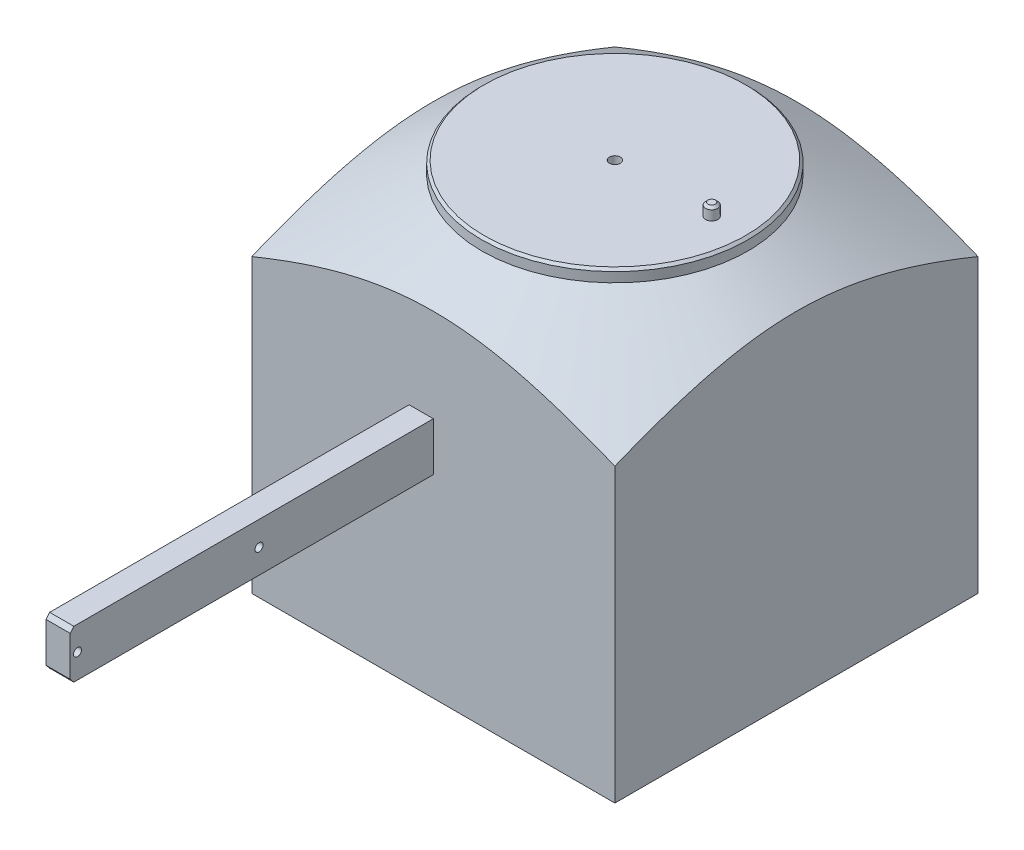
SolidWorks part; units mm, degrees
ref_plane "Płaszczyzna przednia" through (0, 0, 0) normal (0, 0, 1) x (1, 0, 0)
ref_plane "Płaszczyzna górna" through (0, 0, 0) normal (0, 1, 0) x (1, 0, 0)
ref_plane "Płaszczyzna prawa" through (0, 0, 0) normal (1, 0, 0) x (0, 0, -1)
sketch "Sketch1" plane through (0, 0, 0) normal (0, 1, 0) x (1, 0, 0)
  line L1 (-150, 150) -> (150, 150)
  line L2 (-150, 150) -> (-150, -150)
  line L3 (-150, -150) -> (150, -150)
  line L4 (150, 150) -> (150, -150)
  line L5 (-150, 150) -> (150, -150) construction
  line L6 (-150, -150) -> (150, 150) construction
  point P0 (0, 0)
  dimension "D1" = 300
extrude "Boss-Extrude1" add sketch "Sketch1" along normal blind 300
sketch "Sketch2" plane through (0, 0, 0) normal (0, 0, 1) x (1, 0, 0)
  line L0 (0, 394.1921) -> (0, -74.9014) construction
  line L1 (110, 300) -> (250, 219.171)
  line L2 (-150, 300) -> (150, 300) construction
  line L4 (110, 300) -> (250, 300)
  line L5 (250, 300) -> (250, 219.171)
  dimension "D1" = 30
  dimension "D2" = 500
  dimension "D3" = 220
revolve "Cut-Revolve1" cut sketch "Sketch2" angle 360 about L0
sketch "Sketch3" plane through (0, 300, 0) normal (0, 1, 0) x (1, 0, 0)
  circle A0 centre (0, 0) radius 110
  circle A1 centre (0, 0) radius 110 construction
extrude "Boss-Extrude2" add sketch "Sketch3" along normal blind 10
sketch "Sketch4" plane through (0, 310, 0) normal (0, 1, 0) x (1, 0, 0)
  circle A0 centre (80, 0) radius 5
  circle A1 centre (0, 0) radius 110 construction
  dimension "D1" = 10
  dimension "D2" = 80
extrude "Boss-Extrude3" add sketch "Sketch4" along normal blind 10
chamfer "Chamfer1" distance 2 angle 45 1 edges at (0, 310, 110)
chamfer "Chamfer2" distance 2 angle 45 1 edges at (80, 320, 5)
hole_wizard "M10x1.0 Tapped Hole1" positions "Sketch6" profile "Sketch5" tap size "M10x1.0" standard "DIN"
sketch "Sketch6" plane through (0, 310, 0) normal (0, 1, 0) x (1, 0, 0)
  point P0 (0, 0)
cosmetic thread "Hole Thread1" parameters "D1"=3.05, "D2"=10
sketch "Sketch5" plane through (0, 310, 0) normal (1, 0, 0) x (0, 0, 1)
  line L0 (0, 0) -> (0, 25.7039)
  line L1 (0, 25.7039) -> (4.5, 23)
  line L2 (4.5, 23) -> (4.5, 0)
  line L5 (4.5, 0) -> (0, 0)
  line L10 (0, 25.7039) -> (-4.5, 23) construction
  line L11 (0, -6.35) -> (0, 107.95) construction
  dimension "Tap Drill Dia." = 9
  dimension "Tap Drill Depth" = 23
  dimension "Drill Angle" = 118
sketch "Sketch7" plane through (0, 0, 150) normal (0, 0, 1) x (1, 0, 0)
  line L0 (-20, 180) -> (0, 180) construction
  line L1 (0, 200) -> (-20, 200)
  line L2 (0, 200) -> (0, 160)
  line L3 (0, 160) -> (-20, 160)
  line L4 (-20, 200) -> (-20, 160)
  dimension "D1" = 40
  dimension "D2" = 180
  dimension "D3" = 20
extrude "Boss-Extrude4" add sketch "Sketch7" along normal blind 300
chamfer "Chamfer3" distance 3 angle 50 2 edges at (-10, 160, 450) (-10, 200, 450)
hole_wizard "M6 Clearance Hole1" positions "Sketch9" profile "Sketch8" hole size "M6" standard "DIN" end condition through all
sketch "Sketch9" plane through (0, 0, 0) normal (1, 0, 0) x (0, 0, -1)
  line L0 (-369, 208.3414) -> (-369, 147.6119) construction
  line L2 (-450, 163.5753) -> (-450, 196.4247) construction
  line L3 (-341.4135, 180) -> (-248.5516, 180) construction
  line L5 (-447, 160) -> (-150, 160) construction
  line L6 (-447, 200) -> (-150, 200) construction
  point P0 (-444, 180)
  point P2 (-294, 180)
  dimension "D1" = 150
  dimension "D2" = 6
sketch "Sketch8" plane through (0, 180, 444) normal (0, 1, 0) x (0, 0, -1)
  line L0 (0, 0) -> (0, 150)
  line L1 (0, 150) -> (3.3, 150)
  line L2 (3.3, 150) -> (3.3, 0)
  line L5 (3.3, 0) -> (0, 0)
  line L11 (0, -6.35) -> (0, 107.95) construction
  dimension "Thru Hole Dia." = 6.6
  dimension "Thru Hole Depth" = 150
